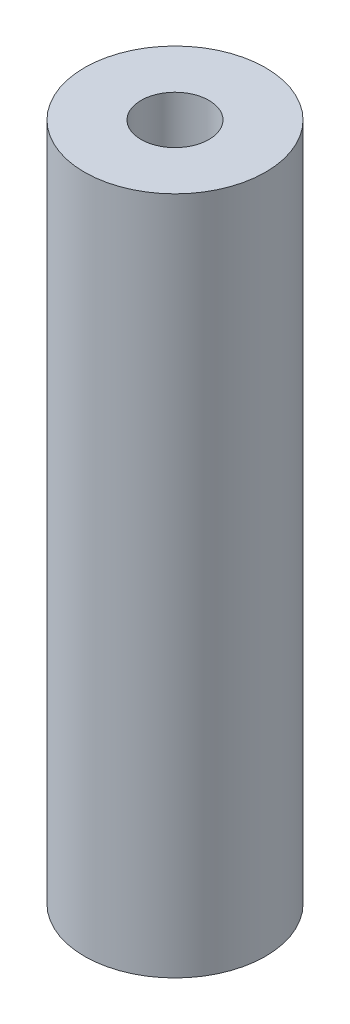
SolidWorks part; units mm, degrees
ref_plane "Front Plane" through (0, 0, 0) normal (0, 0, 1) x (1, 0, 0)
ref_plane "Top Plane" through (0, 0, 0) normal (0, 1, 0) x (1, 0, 0)
ref_plane "Right Plane" through (0, 0, 0) normal (1, 0, 0) x (0, 0, -1)
sketch "Sketch1" plane through (0, 0, 0) normal (0, 1, 0) x (1, 0, 0)
  circle A0 centre (0, 0) radius 4
  circle A1 centre (0, 0) radius 1.5
  dimension "D1" = 8
  dimension "D2" = 3
extrude "Boss-Extrude1" add sketch "Sketch1" along normal blind 30
